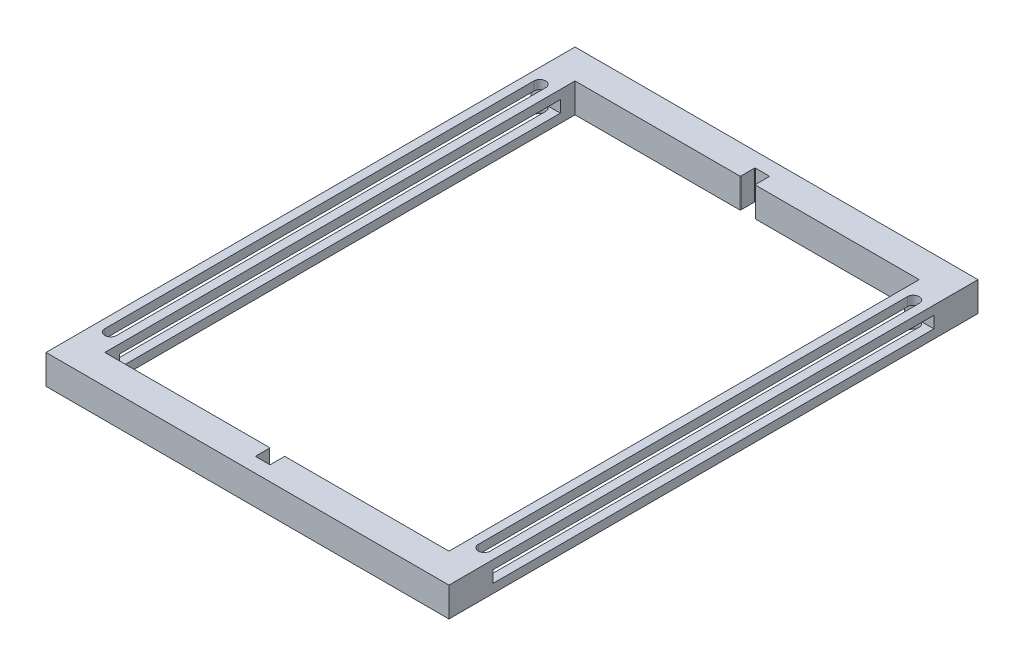
SolidWorks part; units mm, degrees
ref_plane "Front Plane" through (0, 0, 0) normal (0, 0, 1) x (1, 0, 0)
ref_plane "Top Plane" through (0, 0, 0) normal (0, 1, 0) x (1, 0, 0)
ref_plane "Right Plane" through (0, 0, 0) normal (1, 0, 0) x (0, 0, -1)
sketch "Sketch1" plane through (0, 0, 0) normal (0, 1, 0) x (1, 0, 0)
  line L0 (6.2036, 8.7622) -> (143.3036, 8.7622)
  line L1 (6.2036, -171.2378) -> (143.3036, -171.2378)
  line L2 (6.2036, 8.7622) -> (6.2036, -171.2378)
  line L3 (143.3036, -171.2378) -> (143.3036, 8.7622)
  line L4 (16.2036, -1.2378) -> (72.1788, -1.2378)
  line L5 (133.3036, -161.2378) -> (133.3036, -1.2378)
  line L6 (16.2036, -161.2378) -> (72.1788, -161.2378)
  line L7 (16.2036, -1.2378) -> (16.2036, -161.2378)
  line L8 (72.4288, 8.8199) -> (72.4288, -1.2378) construction
  line L9 (72.4288, 3.5122) -> (72.4288, -0.9878)
  line L10 (77.4288, 3.5122) -> (77.4288, -0.9878)
  line L11 (72.6788, 3.7622) -> (77.1788, 3.7622)
  line L13 (72.6788, -166.2378) -> (77.1788, -166.2378)
  line L15 (11.2036, 3.7622) -> (138.3036, 3.7622) construction
  line L16 (77.4288, 8.8199) -> (77.4288, -1.2378) construction
  line L17 (77.6788, -1.2378) -> (133.3036, -1.2378)
  line L18 (16.2036, -1.2378) -> (133.3036, -1.2378) construction
  line L19 (11.2036, -166.2378) -> (138.3036, -166.2378) construction
  line L20 (72.4288, -161.4878) -> (72.4288, -165.9878)
  line L21 (77.4288, -161.4878) -> (77.4288, -165.9878)
  line L22 (72.4288, -161.2378) -> (72.4288, -171.2378) construction
  line L23 (77.4288, -161.2378) -> (77.4288, -171.2378) construction
  line L24 (11.2036, 3.7622) -> (11.2036, -166.2378) construction
  line L25 (138.3036, -166.2378) -> (138.3036, 3.7622) construction
  line L26 (77.6788, -161.2378) -> (133.3036, -161.2378)
  line L27 (16.2036, -161.2378) -> (133.3036, -161.2378) construction
  line L37 (11.2036, -154.2378) -> (11.2036, -8.2378) construction
  line L38 (9.2036, -154.2378) -> (9.2036, -8.2378)
  line L39 (13.2036, -154.2378) -> (13.2036, -8.2378)
  line L41 (138.3036, -154.2378) -> (138.3036, -8.2378) construction
  line L42 (136.3036, -154.2378) -> (136.3036, -8.2378)
  line L43 (140.3036, -154.2378) -> (140.3036, -8.2378)
  arc A0 (77.6788, -161.2378) -> (77.4288, -161.4878) centre (77.6788, -161.4878) ccw
  arc A1 (77.4288, -165.9878) -> (77.1788, -166.2378) centre (77.1788, -165.9878) cw
  arc A2 (72.4288, -165.9878) -> (72.6788, -166.2378) centre (72.6788, -165.9878) ccw
  arc A3 (72.4288, -161.4878) -> (72.1788, -161.2378) centre (72.1788, -161.4878) ccw
  arc A4 (72.1788, -1.2378) -> (72.4288, -0.9878) centre (72.1788, -0.9878) ccw
  arc A5 (72.4288, 3.5122) -> (72.6788, 3.7622) centre (72.6788, 3.5122) cw
  arc A6 (77.1788, 3.7622) -> (77.4288, 3.5122) centre (77.1788, 3.5122) cw
  arc A7 (77.4288, -0.9878) -> (77.6788, -1.2378) centre (77.6788, -0.9878) ccw
  arc A8 (9.2036, -154.2378) -> (13.2036, -154.2378) centre (11.2036, -154.2378) ccw
  arc A9 (13.2036, -8.2378) -> (9.2036, -8.2378) centre (11.2036, -8.2378) ccw
  arc A10 (136.3036, -154.2378) -> (140.3036, -154.2378) centre (138.3036, -154.2378) ccw
  arc A11 (140.3036, -8.2378) -> (136.3036, -8.2378) centre (138.3036, -8.2378) ccw
  point P54 (11.2036, -81.2378)
  point P61 (138.3036, -81.2378)
  dimension "D3" = 0.25
  dimension "D7" = 0.25
  dimension "D1" = 180
  dimension "D2" = 10
  dimension "D4" = 5
  dimension "D5" = 5
  dimension "D6" = 5
extrude "Boss-Extrude1" add sketch "Sketch1" along normal blind 10
sketch "Sketch2" plane through (143.3036, 0, 0) normal (1, 0, 0) x (0, 0, -1)
  line L1 (-6.2378, 0) -> (-6.2378, 10) construction
  line L5 (-156.2378, 10) -> (-156.2378, 0) construction
  line L9 (-156.2378, 7) -> (-6.2378, 7)
  line L10 (-156.2378, 7) -> (-156.2378, 3)
  line L11 (-156.2378, 3) -> (-6.2378, 3)
  line L12 (-6.2378, 7) -> (-6.2378, 3)
extrude "Cut-Extrude1" cut sketch "Sketch2" against normal blind 160
